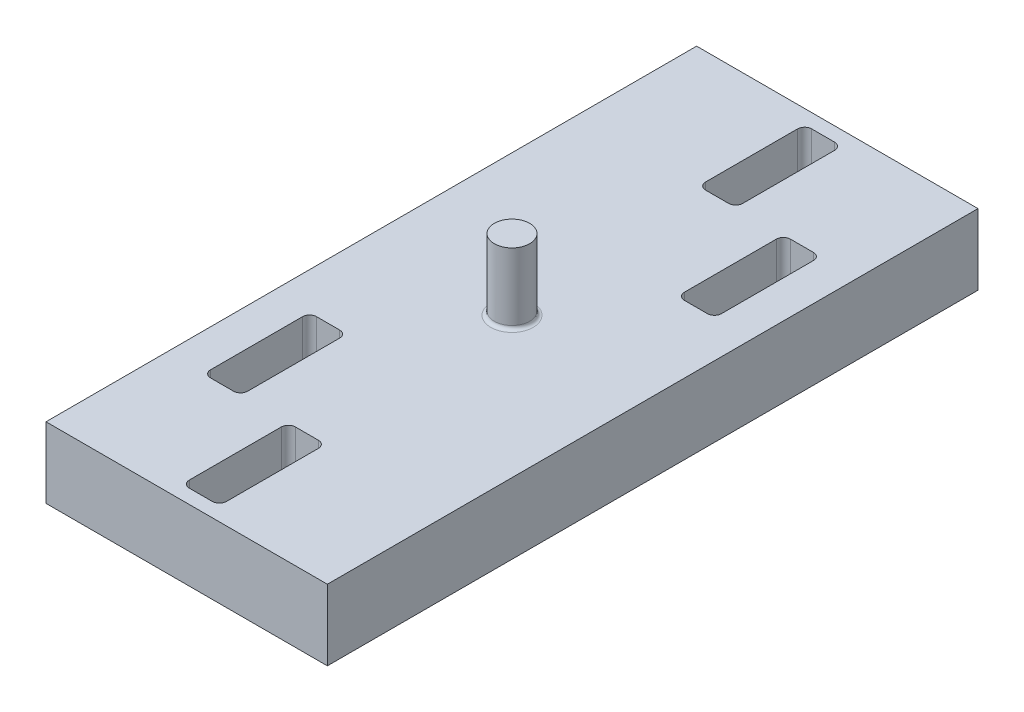
SolidWorks part; units mm, degrees
ref_plane "Front Plane" through (0, 0, 0) normal (0, 0, 1) x (1, 0, 0)
ref_plane "Top Plane" through (0, 0, 0) normal (0, 1, 0) x (1, 0, 0)
ref_plane "Right Plane" through (0, 0, 0) normal (1, 0, 0) x (0, 0, -1)
sketch "10" plane through (0, 0, 0) normal (0, 1, 0) x (1, 0, 0)
  line L0 (-15, 31.5) -> (15, 31.5) construction
  line L1 (-14.8938, 29.7182) -> (14.8938, 33.2818)
  line L2 (-14.8938, 29.7182) -> (-12, 15)
  line L3 (14.8938, 33.2818) -> (12, 48)
  line L4 (-12, 15) -> (0, 15)
  line L5 (12, 48) -> (0, 48)
  line L6 (0, 48) -> (0, 63)
  line L7 (0, 15) -> (0, 0)
  point P4 (0, 31.5)
  point P5 (0, 31.5)
  dimension "D1" = 15
  dimension "D2" = 12
  dimension "D3" = 15
  dimension "D4" = 30
  dimension "D5" = 30
  dimension "D6" = 15
  dimension "D7" = 0
  dimension "D8" = 0
  dimension "D9" = 31.5
sketch "01" plane through (0, 0, 0) normal (0, 1, 0) x (1, 0, 0)
  line L0 (-15, 31.5) -> (15, 31.5) construction
  line L1 (-9.3393, 19.7621) -> (9.3393, 43.2379)
  line L2 (-9.3393, 19.7621) -> (-12, 5)
  line L3 (9.3393, 43.2379) -> (12, 58)
  line L4 (-12, 5) -> (0, 5)
  line L5 (12, 58) -> (0, 58)
  line L6 (0, 58) -> (0, 73)
  line L7 (0, 5) -> (0, -10)
  point P4 (0, 31.5)
  point P5 (0, 31.5)
  dimension "D1" = 30
  dimension "D2" = 15
  dimension "D3" = 12
  dimension "D4" = 15
  dimension "D5" = 30
  dimension "D6" = 0
  dimension "D7" = 41.5
  dimension "D8" = 0
  dimension "D9" = 15
sketch "Sketch2" plane through (0, 0, 0) normal (0, 1, 0) x (1, 0, 0)
  line L1 (-19.8938, 77.5) -> (0, 77.5)
  line L2 (-19.8938, 77.5) -> (-19.8938, -14.5)
  line L3 (-19.8938, -14.5) -> (0, -14.5)
  line L9 (-15, 31.5) -> (15, 31.5) construction
  line L24 (0, 77.5) -> (0, 75.5)
  line L25 (-2.625, 73) -> (-2.625, 63)
  line L26 (0, 75.5) -> (-2.625, 75.5)
  line L27 (-2.625, 75.5) -> (-2.625, 73)
  line L28 (0, 60.5) -> (-2.625, 60.5)
  line L29 (-2.625, 60.5) -> (-2.625, 63)
  line L32 (0, 60.375) -> (0, 2.5)
  line L34 (0, 60.5) -> (0, 60.375)
  line L35 (-2.625, 0) -> (-2.625, -10)
  line L36 (0, 2.5) -> (-2.625, 2.5)
  line L37 (-2.625, 2.5) -> (-2.625, 0)
  line L38 (0, -12.5) -> (-2.625, -12.5)
  line L39 (-2.625, -12.5) -> (-2.625, -10)
  line L41 (0, -12.5) -> (0, -14.5)
  circle A7 centre (-14.8938, 29.7182) radius 5 construction
  circle A19 centre (0, 73) radius 2.625 construction
  circle A21 centre (0, 63) radius 2.625 construction
  circle A22 centre (0, 73) radius 2.5 construction
  circle A23 centre (0, 63) radius 2.5 construction
  circle A24 centre (0, -10) radius 2.625 construction
  circle A25 centre (0, 0) radius 2.625 construction
  circle A26 centre (0, 0) radius 2.5 construction
  circle A27 centre (0, -10) radius 2.5 construction
  dimension "D2" = 5.25
  dimension "D3" = 5.25
  dimension "D4" = 5
  dimension "D5" = 5
  dimension "D8" = 10
  dimension "D7" = 10
  dimension "D9" = 5.25
  dimension "D12" = 5.25
  dimension "D14" = 5
  dimension "D15" = 5
  dimension "D6" = 2
  dimension "D10" = 19.8938
  dimension "D11" = 5
  dimension "D13" = 19.8938
  dimension "D16" = 10
  dimension "D17" = 2
  dimension "D18" = 57.875
extrude "Boss-Extrude1" add sketch "Sketch2" along normal blind 10 contours L2 L3 L41 L38 L39 L35 L37 L36 L32 L34 L28 L29 L25 L27 L26 L24 L1
fillet "Fillet2" radius 1 4 edges at (-2.625, 5, 12.5) (-2.625, 5, -2.5) (-2.625, 5, -60.5) (-2.625, 5, -75.5)
mirror "Mirror1" of "Fillet2", "Boss-Extrude1"
sketch "Sketch4" plane through (0, 0, 0) normal (0, 1, 0) x (1, 0, 0)
  line L0 (-14.625, 15) -> (-14.625, 5)
  line L1 (-9.375, 15) -> (-9.375, 5)
  line L2 (-12, 2.5) -> (-9.375, 2.5)
  line L3 (-9.375, 2.5) -> (-9.375, 5)
  line L4 (-12, 2.5) -> (-14.625, 2.5)
  line L5 (-14.625, 2.5) -> (-14.625, 5)
  line L6 (-12, 17.5) -> (-9.375, 17.5)
  line L7 (-9.375, 17.5) -> (-9.375, 15)
  line L9 (-12, 17.5) -> (-14.625, 17.5)
  line L10 (-14.625, 17.5) -> (-14.625, 15)
  line L12 (9.375, 58) -> (9.375, 48)
  line L13 (14.625, 58) -> (14.625, 48)
  line L16 (12, 60.5) -> (9.375, 60.5)
  line L17 (9.375, 60.5) -> (9.375, 58)
  line L19 (12, 60.5) -> (14.625, 60.5)
  line L20 (14.625, 60.5) -> (14.625, 58)
  line L21 (12, 45.5) -> (14.625, 45.5)
  line L22 (14.625, 45.5) -> (14.625, 48)
  line L23 (12, 45.5) -> (9.375, 45.5)
  line L24 (9.375, 45.5) -> (9.375, 48)
  circle A0 centre (-12, 5) radius 2.625 construction
  circle A1 centre (-12, 15) radius 2.625 construction
  circle A14 centre (-12, 15) radius 2.5 construction
  circle A15 centre (-12, 5) radius 2.5 construction
  circle A16 centre (12, 48) radius 2.625 construction
  circle A17 centre (12, 48) radius 2.5 construction
  circle A18 centre (12, 58) radius 2.5 construction
  circle A19 centre (12, 58) radius 2.625 construction
  dimension "D1" = 5.25
  dimension "D2" = 5
extrude "Cut-Extrude1" cut sketch "Sketch4" along normal through all
fillet "Fillet3" radius 1 8 edges at (9.375, 5, -45.5) (14.625, 5, -45.5) (9.375, 5, -60.5) (14.625, 5, -60.5) (-14.625, 5, -2.5) (-9.375, 5, -2.5) (-9.375, 5, -17.5) (-14.625, 5, -17.5)
sketch "Sketch5" plane through (0, 10, 0) normal (0, 1, 0) x (1, 0, 0)
  line L0 (-14.8938, 29.7182) -> (14.8938, 33.2818) construction
  circle A0 centre (0, 31.5) radius 2.5
  dimension "D1" = 5
extrude "Boss-Extrude2" add sketch "Sketch5" along normal blind 10
fillet "Fillet1" radius 0.5 1 edges at (0, 10, -34)
sketch "Sketch6" plane through (0, 10, 0) normal (0, 1, 0) x (1, 0, 0)
  line L0 (19.8938, 77.5) -> (19.8938, 67.6092)
  line L9 (19.8938, 77.5) -> (19.8938, -14.5) construction
  line L10 (19.8938, 67.6092) -> (4.4671, 67.6092)
  line L11 (4.4671, 67.6092) -> (4.4671, 43.5)
  line L12 (-6.625, 43.5) -> (55.225, 43.5) construction
  line L13 (4.4671, 43.5) -> (-6.625, 43.5)
  line L15 (-19.8938, 77.5) -> (19.8938, 77.5) construction
  line L16 (-6.625, 124.9007) -> (-6.625, 43.5) construction
  line L17 (-6.625, 77.5) -> (19.8938, 77.5)
  line L18 (-6.625, 43.5) -> (-19.8938, 43.5)
  line L19 (-19.8938, 77.5) -> (-19.8938, -14.5) construction
  line L20 (-19.8938, 43.5) -> (-19.8938, 77.5)
  line L21 (-19.8938, 77.5) -> (-6.625, 77.5)
